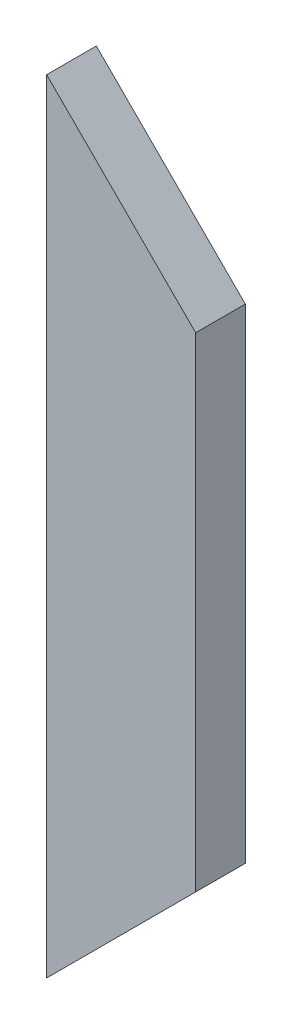
SolidWorks part; units mm, degrees
material "AISI 1020"
ref_plane "Front Plane" through (0, 0, 0) normal (0, 0, 1) x (1, 0, 0)
ref_plane "Top Plane" through (0, 0, 0) normal (0, 1, 0) x (1, 0, 0)
ref_plane "Right Plane" through (0, 0, 0) normal (1, 0, 0) x (0, 0, -1)
sketch "Sketch1" plane through (0, 0, 0) normal (0, 0, 1) x (1, 0, 0)
  line L1 (-38.1, -200.025) -> (38.1, -200.025)
  line L2 (-38.1, -200.025) -> (-38.1, 200.025)
  line L3 (-38.1, 200.025) -> (38.1, 200.025)
  line L4 (38.1, -200.025) -> (38.1, 200.025)
  line L5 (-38.1, -200.025) -> (38.1, 200.025) construction
  line L6 (-38.1, 200.025) -> (38.1, -200.025) construction
  point P0 (0, 0)
  dimension "D1" = 400.05
  dimension "D2" = 76.2
extrude "Boss-Extrude1" add sketch "Sketch1" along normal blind 25.4 contours L3 L4 L1 L2
sketch "Sketch2" plane through (0, 0, 0) normal (0, 0, 1) x (1, 0, 0)
  line L0 (-38.1, 200.025) -> (38.1, 123.825)
  line L1 (38.1, -200.025) -> (38.1, 200.025) construction
  line L2 (38.1, 123.825) -> (38.1, 200.025)
  line L3 (38.1, 200.025) -> (-38.1, 200.025)
  line L4 (-38.1, -200.025) -> (38.1, -123.825)
  line L5 (38.1, -123.825) -> (38.1, -200.025)
  line L6 (38.1, -200.025) -> (-38.1, -200.025)
extrude "Cut-Extrude1" cut sketch "Sketch2" along normal blind 25.4
equation "\"A\"= 100"
equation "\"B\"= 100"
equation "\"C\"= 100"
equation "\"D\"= 100"
equation "\"E\"= 100"
